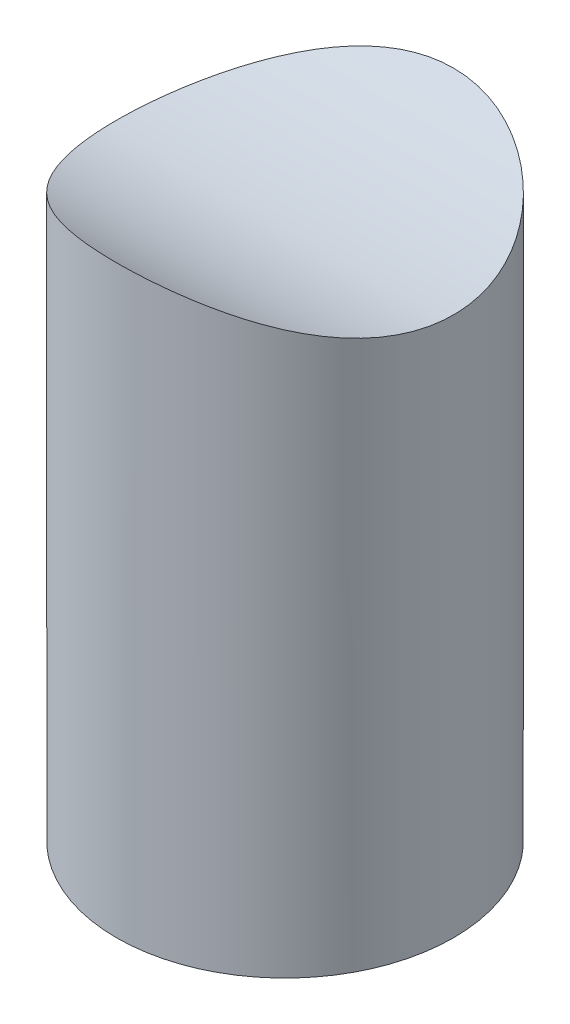
SolidWorks part; units mm, degrees
ref_plane "Front" through (0, 0, 0) normal (0, 0, 1) x (1, 0, 0)
ref_plane "Top" through (0, 0, 0) normal (0, 1, 0) x (1, 0, 0)
ref_plane "Right" through (0, 0, 0) normal (1, 0, 0) x (0, 0, -1)
sketch "Croquis2" plane through (0, 0, 0) normal (0, 1, 0) x (1, 0, 0)
  circle A0 centre (0, 0) radius 25
  dimension "D1" = 50
extrude "Saliente-Extruir2" add sketch "Croquis2" along normal mid plane 100
sketch "Croquis3" plane through (0, 0, 0) normal (1, 0, 0) x (0, 0, -1)
  line L0 (25, 50) -> (-25, 50) construction
  line L1 (0, 50) -> (0, -50) construction
  circle A0 centre (0, 80) radius 50
  dimension "D1" = 100
  dimension "D2" = 30
extrude "Cortar-Extruir1" cut sketch "Croquis3" against normal through all both and the other way through all
